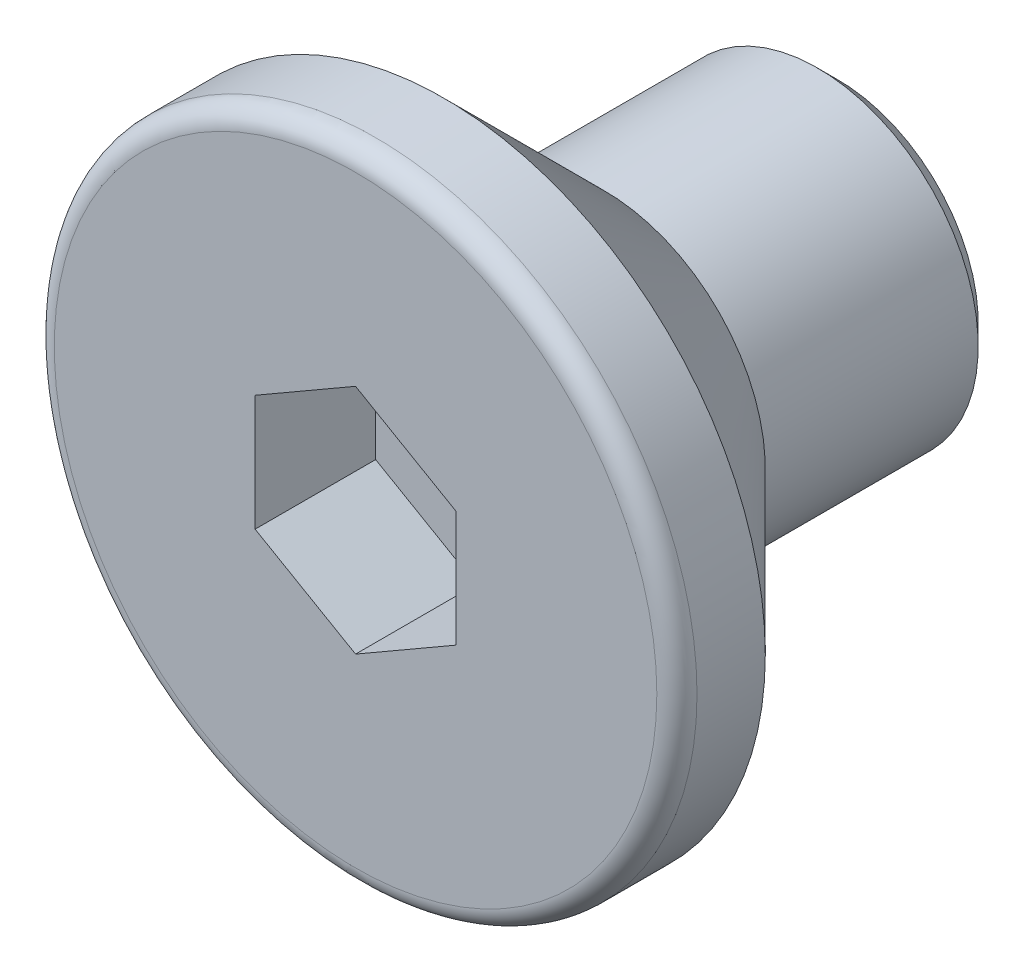
SolidWorks part; units mm, degrees
ref_plane "前视基准面" through (0, 0, 0) normal (0, 0, 1) x (1, 0, 0)
ref_plane "上视基准面" through (0, 0, 0) normal (0, 1, 0) x (1, 0, 0)
ref_plane "右视基准面" through (0, 0, 0) normal (1, 0, 0) x (0, 0, -1)
sketch "草图1" plane through (0, 0, 0) normal (1, 0, 0) x (0, 0, -1)
  line L0 (-6, 0) -> (-6, 8)
  line L1 (-6, 8) -> (-3.8, 8)
  line L2 (-3.8, 8) -> (0.2, 4)
  line L3 (0.2, 4) -> (6, 4)
  line L4 (6, 4) -> (6, 0)
  line L5 (6, 0) -> (-6, 0)
  dimension "D1" = 4
  dimension "D2" = 12
  dimension "D3" = 45
  dimension "D4" = 6.2
  dimension "D5" = 8
revolve "旋转1" add sketch "草图1" angle 360 about L5
sketch "草图2" plane through (0, 0, 6) normal (0, 0, 1) x (1, 0, 0)
  line L1 (0, 2.8868) -> (-2.5, 1.4434)
  line L2 (-2.5, 1.4434) -> (-2.5, -1.4434)
  line L3 (-2.5, -1.4434) -> (0, -2.8868)
  line L4 (0, -2.8868) -> (2.5, -1.4434)
  line L5 (2.5, -1.4434) -> (2.5, 1.4434)
  line L6 (2.5, 1.4434) -> (0, 2.8868)
  circle A0 centre (0, 0) radius 2.5 construction
  dimension "D1" = 5
extrude "切除-拉伸1" cut sketch "草图2" against normal blind 3
fillet "圆角1" radius 0.5 1 edges at (-8, 0, 6)
chamfer "倒角1" distance 0.5 angle 45 1 edges at (-4, 0, -6)
